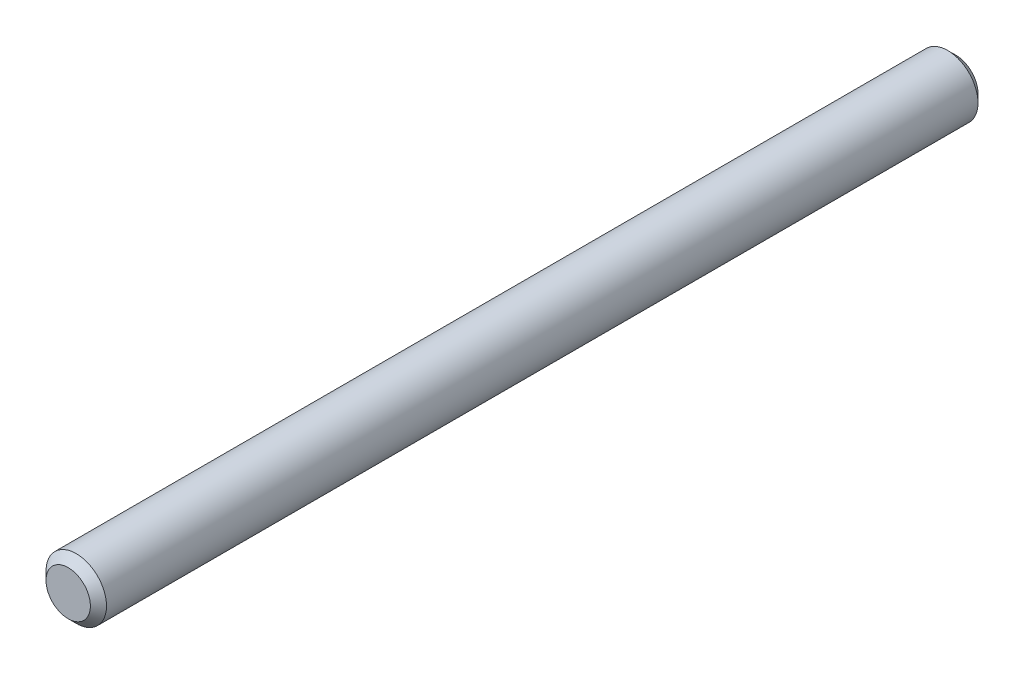
SolidWorks part; units mm, degrees
ref_plane "Front Plane" through (0, 0, 0) normal (0, 0, 1) x (1, 0, 0)
ref_plane "Top Plane" through (0, 0, 0) normal (0, 1, 0) x (1, 0, 0)
ref_plane "Right Plane" through (0, 0, 0) normal (1, 0, 0) x (0, 0, -1)
sketch "Sketch1" plane through (0, 0, 0) normal (0, 0, 1) x (1, 0, 0)
  circle A0 centre (0, 0) radius 7.5
  dimension "D1" = 15
extrude "Boss-Extrude1" add sketch "Sketch1" along normal mid plane 220
chamfer "Chamfer1" distance 2 1 edges at (7.5, 0, -110)
chamfer "Chamfer2" distance 2 1 edges at (7.5, 0, 110)
